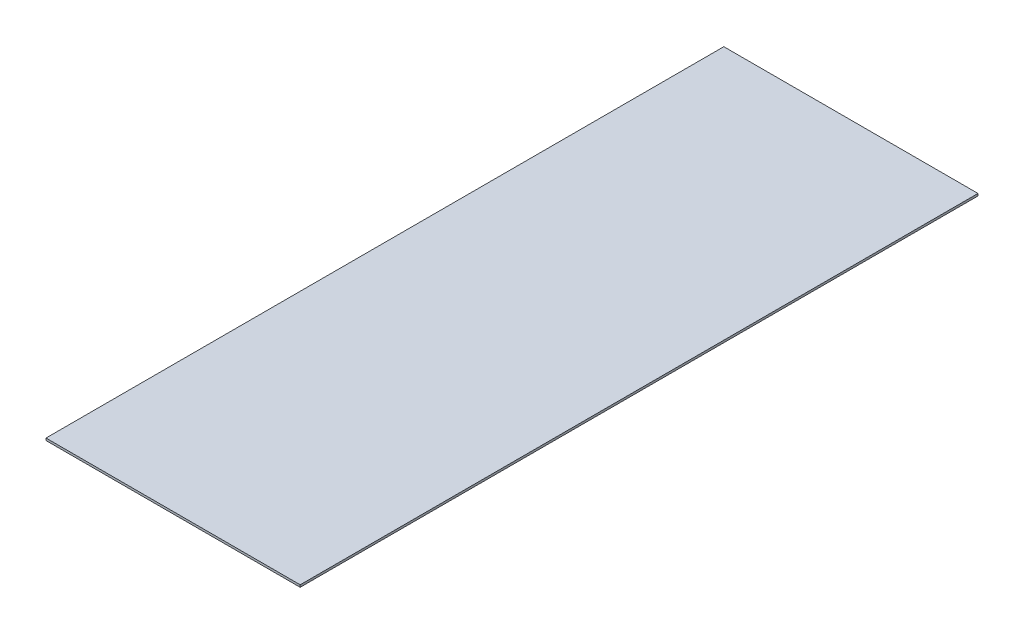
SolidWorks part; units mm, degrees
material "ASTM A36 Acero"
ref_plane "Alzado" through (0, 0, 0) normal (0, 0, 1) x (1, 0, 0)
ref_plane "Planta" through (0, 0, 0) normal (0, 1, 0) x (1, 0, 0)
ref_plane "Vista lateral" through (0, 0, 0) normal (1, 0, 0) x (0, 0, -1)
sketch "Croquis1" plane through (0, 0, 0) normal (0, 1, 0) x (1, 0, 0)
  line L1 (-457.2, -1219.2) -> (457.2, -1219.2)
  line L2 (-457.2, -1219.2) -> (-457.2, 1219.2)
  line L3 (-457.2, 1219.2) -> (457.2, 1219.2)
  line L4 (457.2, -1219.2) -> (457.2, 1219.2)
  line L5 (-457.2, -1219.2) -> (457.2, 1219.2) construction
  line L6 (-457.2, 1219.2) -> (457.2, -1219.2) construction
  point P0 (0, 0)
  dimension "D1" = 2438.4
  dimension "D2" = 914.4
extrude "Saliente-Extruir1" add sketch "Croquis1" along normal blind 7.9
